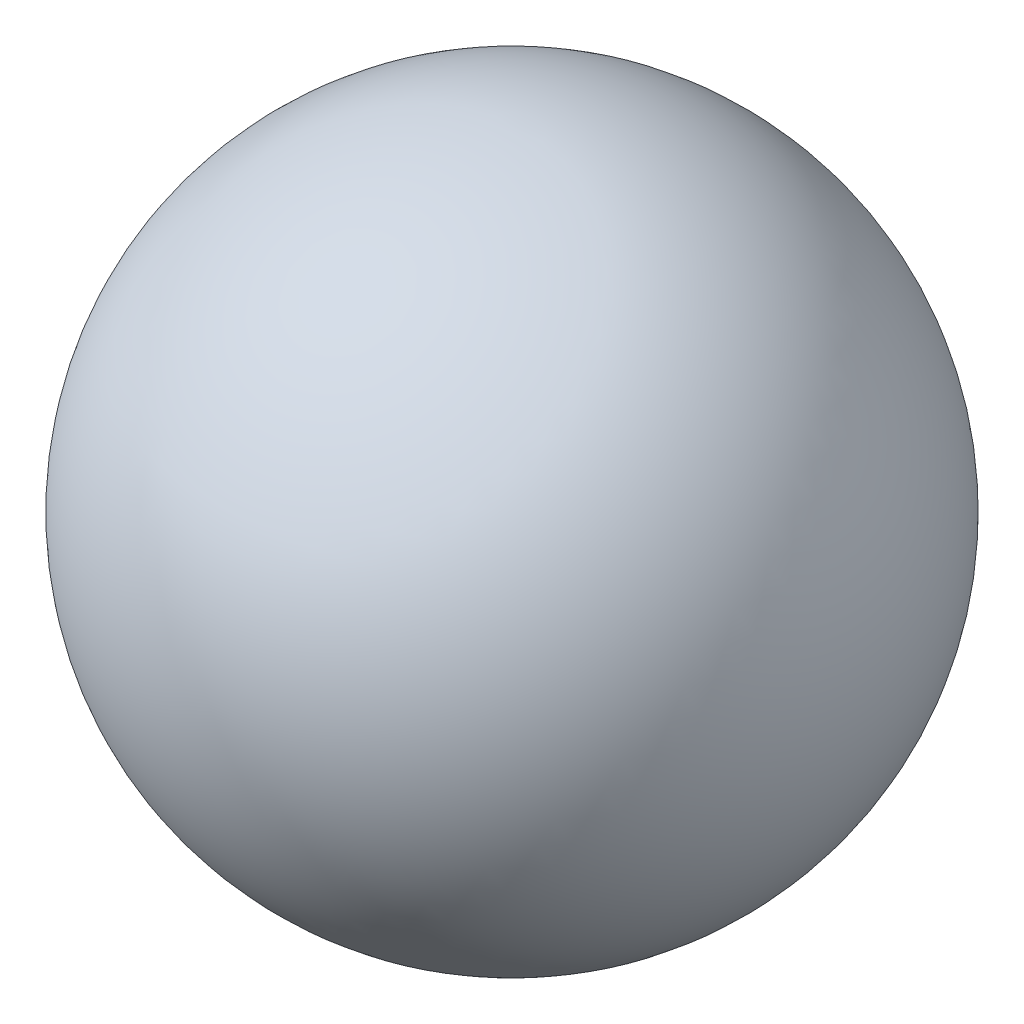
SolidWorks part; units mm, degrees
ref_plane "前视基准面" through (0, 0, 0) normal (0, 0, 1) x (1, 0, 0)
ref_plane "上视基准面" through (0, 0, 0) normal (0, 1, 0) x (1, 0, 0)
ref_plane "右视基准面" through (0, 0, 0) normal (1, 0, 0) x (0, 0, -1)
sketch "草图1" plane through (0, 0, 0) normal (0, 0, 1) x (1, 0, 0)
  line L0 (0, 0) -> (0, 12)
  line L1 (0, 12) -> (0, 0)
  line L2 (0, -12) -> (0, 0)
  arc A0 (0, 12) -> (0, -12) centre (0, 0) cw
  dimension "D1" = 12
  dimension "D2" = 12
revolve "旋转1" add sketch "草图1" angle 360 about L2
scale "缩放比例1" scale about centroid uniform scaling yes scale factor 0.169231
